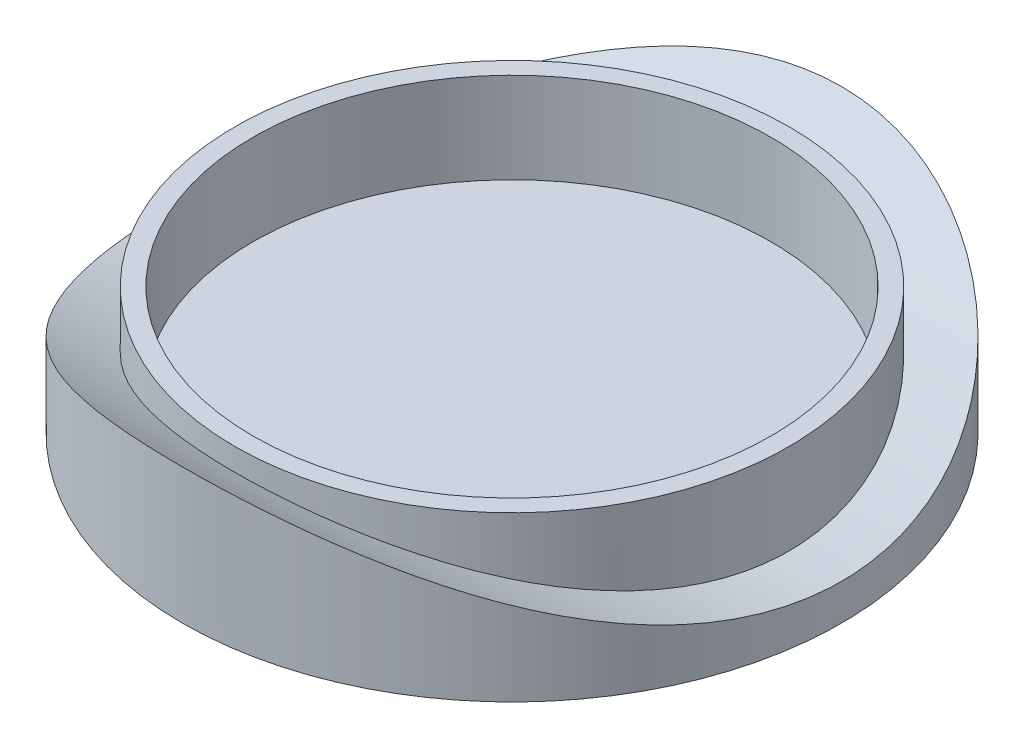
SolidWorks part; units mm, degrees
ref_plane "정면" through (0, 0, 0) normal (0, 0, 1) x (1, 0, 0)
ref_plane "윗면" through (0, 0, 0) normal (0, 1, 0) x (1, 0, 0)
ref_plane "우측면" through (0, 0, 0) normal (1, 0, 0) x (0, 0, -1)
sketch "스케치1" plane through (0, 0, 0) normal (0, 1, 0) x (1, 0, 0)
  circle A0 centre (0, 0) radius 18.2
  dimension "D1" = 36.4
extrude "보스-돌출1" add sketch "스케치1" along normal blind 10
sketch "스케치3" plane through (0, 0, 0) normal (1, 0, 0) x (0, 0, -1)
  line L0 (0, 0) -> (0, 35) construction
  circle A0 centre (0, 35) radius 33
  point P3 (0, 2)
  dimension "D2" = 66
  dimension "D1" = 2
extrude "컷-돌출1" cut sketch "스케치3" against normal through all both and the other way through all
sketch "스케치4" plane through (0, 0, 0) normal (0, 1, 0) x (1, 0, 0)
  circle A0 centre (0, 0) radius 15.3
  dimension "D1" = 30.6
extrude "보스-돌출2" add sketch "스케치4" along normal blind 7
sketch "스케치5" plane through (0, 7, 0) normal (0, 1, 0) x (1, 0, 0)
  circle A0 centre (0, 0) radius 14.3
  circle A1 centre (0, 0) radius 15.3 construction
  dimension "D1" = 1
extrude "컷-돌출2" cut sketch "스케치5" against normal blind 5
